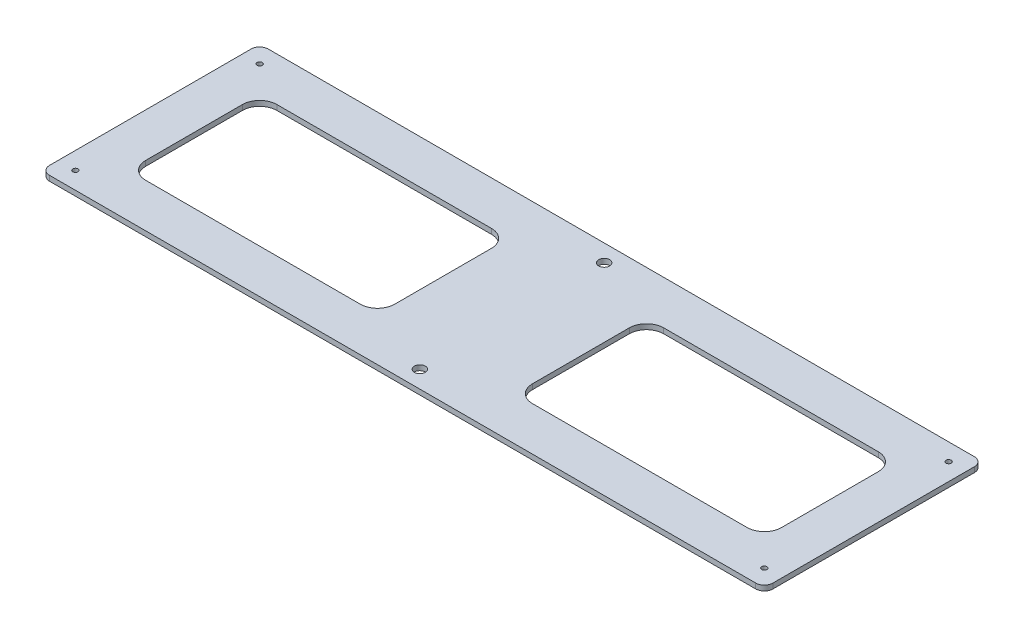
SolidWorks part; units mm, degrees
ref_plane "Front Plane" through (0, 0, 0) normal (0, 0, 1) x (1, 0, 0)
ref_plane "Top Plane" through (0, 0, 0) normal (0, 1, 0) x (1, 0, 0)
ref_plane "Right Plane" through (0, 0, 0) normal (1, 0, 0) x (0, 0, -1)
sketch "Sketch1" plane through (0, 0, 0) normal (0, 1, 0) x (1, 0, 0)
  line L1 (-210, 63.5) -> (210, 63.5)
  line L2 (-210, 63.5) -> (-210, -63.5)
  line L3 (-210, -63.5) -> (210, -63.5)
  line L4 (210, 63.5) -> (210, -63.5)
  line L5 (-210, 63.5) -> (210, -63.5) construction
  line L6 (-210, -63.5) -> (210, 63.5) construction
  point P0 (0, 0)
  dimension "D1" = 127
  dimension "D2" = 420
extrude "Boss-Extrude1" add sketch "Sketch1" along normal blind 3
fillet "Fillet1" radius 5 4 edges at (-210, 1.5, -63.5) (210, 1.5, -63.5) (210, 1.5, 63.5) (-210, 1.5, 63.5)
sketch "Sketch2" plane through (0, 3, 0) normal (0, 1, 0) x (1, 0, 0)
  line L0 (-205, -63.5) -> (205, -63.5) construction
  line L1 (210, -58.5) -> (210, 58.5) construction
  line L2 (205, 63.5) -> (-205, 63.5) construction
  line L3 (-210, 58.5) -> (-210, -58.5) construction
  circle A0 centre (200, -53.5) radius 1.5
  circle A1 centre (-200, -53.5) radius 1.5
  circle A2 centre (-200, 53.5) radius 1.5
  circle A3 centre (200, 53.5) radius 1.5
  dimension "D1" = 3
  dimension "D2" = 10
  dimension "D3" = 10
  dimension "D4" = 3
  dimension "D5" = 10
  dimension "D6" = 10
  dimension "D7" = 3
  dimension "D8" = 10
  dimension "D9" = 10
  dimension "D10" = 3
  dimension "D11" = 10
  dimension "D12" = 10
extrude "Cut-Extrude1" cut sketch "Sketch2" against normal blind 3
sketch "Sketch3" plane through (0, 3, 0) normal (0, 1, 0) x (1, 0, 0)
  line L0 (210, -58.5) -> (210, 58.5) construction
  line L1 (184.6, -38.1) -> (40, -38.1)
  line L2 (184.6, -38.1) -> (184.6, 38.1)
  line L3 (184.6, 38.1) -> (40, 38.1)
  line L4 (-184.6, -38.1) -> (-184.6, 38.1)
  line L5 (184.6, -38.1) -> (40, -8.2557) construction
  line L6 (184.6, 38.1) -> (40, 8.2557) construction
  line L8 (-205, -63.5) -> (205, -63.5) construction
  line L9 (-40, -38.1) -> (-184.6, -38.1)
  line L11 (40, -38.1) -> (40, 38.1)
  line L13 (-40, -38.1) -> (-40, 38.1)
  line L16 (-40, 8.2557) -> (-184.6, 38.1) construction
  line L17 (-40, -8.2557) -> (-184.6, -38.1) construction
  line L18 (-40, 38.1) -> (-184.6, 38.1)
  point P0 (0, 0)
  point P10 (0, 0)
  dimension "D1" = 25.4
  dimension "D2" = 25.4
  dimension "D3" = 80
extrude "Cut-Extrude2" cut sketch "Sketch3" against normal blind 3
fillet "Fillet2" radius 10 8 edges at (-184.6, 1.5, 38.1) (-184.6, 1.5, -38.1) (-40, 1.5, -38.1) (-40, 1.5, 38.1) (40, 1.5, -38.1) (184.6, 1.5, -38.1) (184.6, 1.5, 38.1) (40, 1.5, 38.1)
sketch "Sketch4" plane through (0, 3, 0) normal (0, 1, 0) x (1, 0, 0)
  line L0 (205, 63.5) -> (-205, 63.5) construction
  line L1 (-205, -63.5) -> (205, -63.5) construction
  circle A0 centre (0, 53.5) radius 3.175
  circle A1 centre (0, -53.5) radius 3.175
  point P6 (0, 63.5)
  dimension "D1" = 6.35
  dimension "D2" = 10
  dimension "D3" = 6.35
  dimension "D4" = 10
extrude "Cut-Extrude3" cut sketch "Sketch4" against normal blind 10
